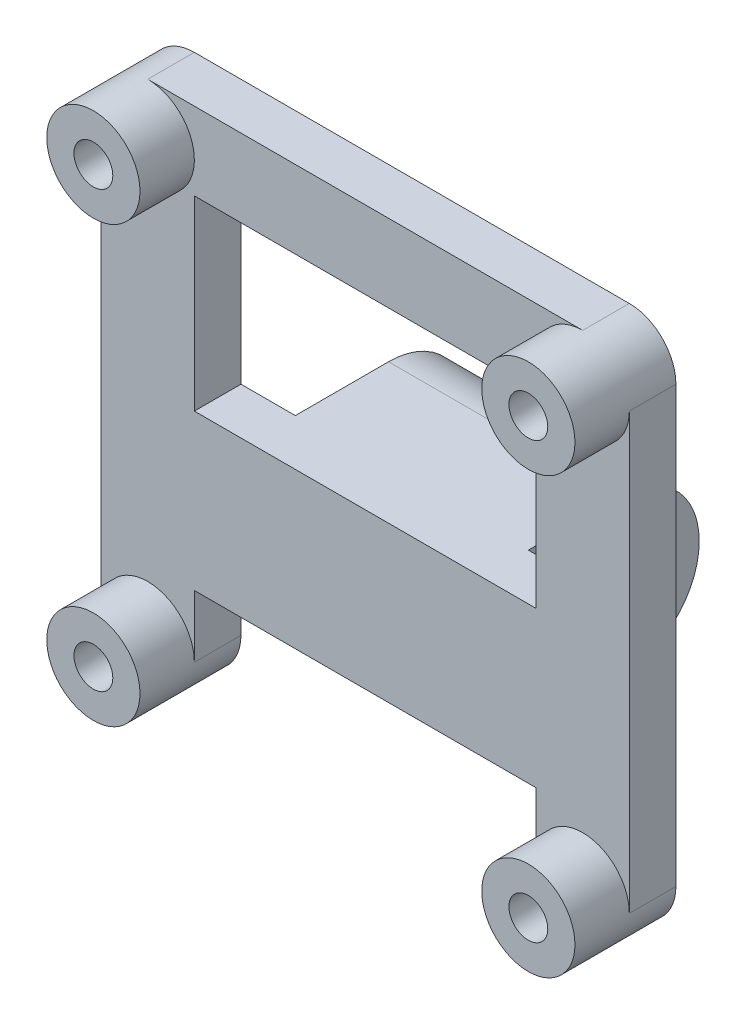
SolidWorks part; units mm, degrees
ref_plane "Plan de face" through (0, 0, 0) normal (0, 0, 1) x (1, 0, 0)
ref_plane "Plan de dessus" through (0, 0, 0) normal (0, 1, 0) x (1, 0, 0)
ref_plane "Plan de droite" through (0, 0, 0) normal (1, 0, 0) x (0, 0, -1)
sketch "Esquisse1" plane through (0, 0, 0) normal (0, 0, 1) x (1, 0, 0)
  line L0 (-11, 0) -> (11, 0) construction
  line L3 (-14, -4) -> (14, -4) construction
  line L4 (14, 10) -> (14, -4) construction
  line L9 (0, 14) -> (0, -14) construction
  line L11 (14, 10) -> (-14, 10) construction
  line L14 (-17, -14) -> (-17, -18)
  line L15 (-11, -18) -> (-11, -14)
  line L16 (-11, -14) -> (11, -14)
  line L17 (11, -14) -> (11, -18)
  line L18 (17, -14) -> (17, -18)
  line L19 (14, -18) -> (-14, -18) construction
  line L21 (-11, 8) -> (11, 8)
  line L24 (14, 13) -> (-14, 13)
  line L25 (11, 8) -> (11, -4)
  line L26 (11, -4) -> (-11, -4)
  line L27 (-11, -4) -> (-11, 8)
  line L28 (14, 10) -> (14, -18) construction
  line L29 (17, 10) -> (17, -14)
  line L30 (-14, 10) -> (-14, -18) construction
  line L31 (-17, -14) -> (-17, 10)
  arc A0 (-17, -18) -> (-11, -18) centre (-14, -18) ccw
  arc A1 (11, -18) -> (17, -18) centre (14, -18) ccw
  arc A5 (14, 13) -> (17, 10) centre (14, 10) cw
  arc A6 (-14, 13) -> (-17, 10) centre (-14, 10) ccw
  point P3 (0, 10)
  dimension "D5" = 3
  dimension "D6" = 3
  dimension "D8" = 22
  dimension "D9" = 3
  dimension "D10" = 3
  dimension "D1" = 4
  dimension "D2" = 5
  dimension "D3" = 10
  dimension "D4" = 6
  dimension "D7" = 28
  dimension "D13" = 10
  dimension "D14" = 28
  dimension "D15" = 12
extrude "Boss.-Extru.1" add sketch "Esquisse1" along normal blind 3
sketch "Esquisse3" plane through (0, 0, 3) normal (0, 0, 1) x (1, 0, 0)
  circle A0 centre (14, 10) radius 3
  circle A1 centre (-14, 10) radius 3
  circle A2 centre (-14, -18) radius 3
  circle A3 centre (14, -18) radius 3
  arc A4 (-14, 13) -> (-17, 10) centre (-14, 10) ccw construction
  dimension "D1" = 6
  dimension "D2" = 6
  dimension "D3" = 6
  dimension "D4" = 6
extrude "Boss.-Extru.3" add sketch "Esquisse3" along normal blind 3.5
sketch "Esquisse4" plane through (0, 0, 6.5) normal (0, 0, 1) x (1, 0, 0)
  circle A0 centre (-14, 10) radius 1.25
  circle A1 centre (14, 10) radius 1.25
  circle A2 centre (-14, -18) radius 1.25
  circle A3 centre (14, -18) radius 1.25
  dimension "D1" = 2.5
  dimension "D2" = 2.5
  dimension "D3" = 2.5
  dimension "D4" = 2.5
extrude "Enlèv. mat.-Extru.1" cut sketch "Esquisse4" against normal through all
sketch "Esquisse5" plane through (0, 0, 0) normal (1, 0, 0) x (0, 0, -1)
  line L0 (6, -14) -> (0, -14)
  line L1 (0, -14) -> (0, -4)
  line L2 (0, -4) -> (6, -4)
  arc A0 (6, -4) -> (6, -14) centre (6, -9) cw
  dimension "D1" = 6
extrude "Boss.-Extru.4" add sketch "Esquisse5" along normal mid plane 15
sketch "Esquisse6" plane through (0, 0, 0) normal (1, 0, 0) x (0, 0, -1)
  circle A0 centre (6, -9) radius 3
  dimension "D1" = 6
extrude "Enlèv. mat.-Extru.2" cut sketch "Esquisse6" against normal through all both and the other way through all
